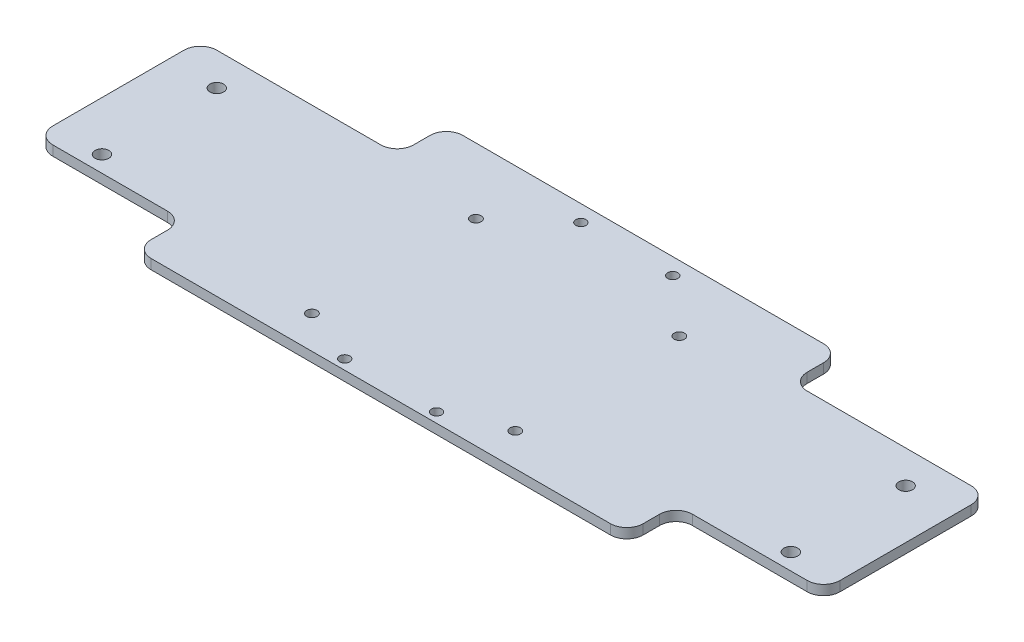
SolidWorks part; units mm, degrees
material "Thornel Mat VMA"
ref_plane "前视基准面" through (0, 0, 0) normal (0, 0, 1) x (1, 0, 0)
ref_plane "上视基准面" through (0, 0, 0) normal (0, 1, 0) x (1, 0, 0)
ref_plane "右视基准面" through (0, 0, 0) normal (1, 0, 0) x (0, 0, -1)
sketch "草图1" plane through (0, 0, 0) normal (0, 1, 0) x (1, 0, 0)
  line L0 (15, 65) -> (15, 0) construction
  line L1 (0, 0) -> (240, 0)
  line L2 (0, 0) -> (0, 65)
  line L3 (0, 65) -> (240, 65)
  line L4 (240, 0) -> (240, 65)
  line L5 (120, 65) -> (120, 0) construction
  line L6 (60, 65) -> (60, 80)
  line L7 (60, 80) -> (180, 80)
  line L8 (120, 65) -> (120, 80) construction
  line L9 (180, 65) -> (180, 80)
  circle A1 centre (15, 55) radius 2.1
  circle A2 centre (225, 20) radius 2.1
  circle A3 centre (15, 20) radius 2.1
  circle A4 centre (225, 55) radius 2.1
  dimension "D4" = 10
  dimension "D5" = 15
  dimension "D6" = 35
  dimension "D2" = 20
  dimension "D8" = 15
  dimension "D1" = 240
  dimension "D3" = 15
  dimension "D7" = 60
extrude "凸台-拉伸1" add sketch "草图1" along normal blind 3 contours L1 L4 L3 L2 A2 A1 A3 A4 | L3 L9 L7 L6
sketch "草图3" plane through (0, 0, 0) normal (0, -1, 0) x (1, 0, 0)
  line L0 (120, -80) -> (120, 0) construction
  line L1 (60, -80) -> (180, -80) construction
  line L2 (0, 0) -> (240, 0) construction
  line L3 (45, 0) -> (45, -15)
  line L4 (106, -3) -> (134, -3) construction
  line L5 (106, -3) -> (106, -75) construction
  line L6 (89, -35) -> (151, -35) construction
  line L7 (151, -60) -> (89, -60) construction
  line L8 (151, -60) -> (151, -10) construction
  line L9 (151, -10) -> (89, -10) construction
  line L10 (89, -60) -> (89, -10) construction
  line L11 (151, -60) -> (89, -10) construction
  line L12 (151, -10) -> (89, -60) construction
  line L13 (106, -75) -> (134, -75) construction
  line L14 (134, -3) -> (134, -75) construction
  line L15 (120, -75) -> (120, -3) construction
  line L16 (106, -39) -> (134, -39) construction
  line L17 (45, -15) -> (0, -15)
  line L18 (0, 0) -> (0, -65) construction
  line L19 (0, -15) -> (0, 0)
  line L20 (0, 0) -> (45, 0)
  line L21 (240, -15) -> (240, 0)
  line L22 (240, 0) -> (195, 0)
  line L23 (195, -15) -> (240, -15)
  line L24 (195, 0) -> (195, -15)
  circle A0 centre (89, -10) radius 1.6
  circle A1 centre (151, -10) radius 1.6
  circle A2 centre (151, -60) radius 1.6
  circle A3 centre (89, -60) radius 1.6
  circle A4 centre (106, -3) radius 1.55
  circle A5 centre (134, -3) radius 1.55
  circle A6 centre (134, -75) radius 1.55
  circle A7 centre (106, -75) radius 1.55
  point P12 (120, -35)
  point P489 (120, -39)
  dimension "D3" = 10
  dimension "D7" = 45
  dimension "D1" = 62
  dimension "D2" = 50
  dimension "D4" = 28
  dimension "D5" = 72
  dimension "D6" = 5
  dimension "D8" = 15
extrude "切除-拉伸2" cut sketch "草图3" against normal through all
fillet "圆角1" radius 5 12 edges at (195, 1.5, 0) (195, 1.5, -15) (240, 1.5, -15) (240, 1.5, -65) (180, 1.5, -65) (180, 1.5, -80) (60, 1.5, -80) (0, 1.5, -65) (60, 1.5, -65) (45, 1.5, -15) (45, 1.5, 0) (0, 1.5, -15)
